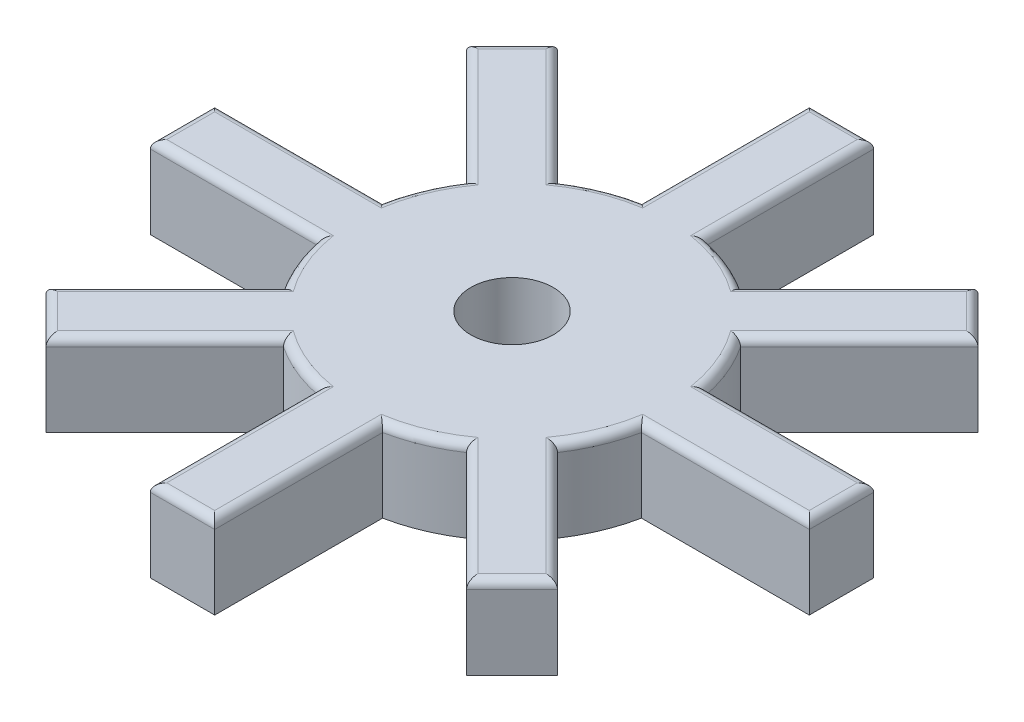
SolidWorks part; units mm, degrees
ref_plane "前视基准面" through (0, 0, 0) normal (0, 0, 1) x (1, 0, 0)
ref_plane "上视基准面" through (0, 0, 0) normal (0, 1, 0) x (1, 0, 0)
ref_plane "右视基准面" through (0, 0, 0) normal (1, 0, 0) x (0, 0, -1)
other "Configuration Table"
sketch "草图1" plane through (0, 0, 0) normal (0, 1, 0) x (1, 0, 0)
  line L0 (0, -20.2795) -> (0, 22.972) construction
  line L1 (1.9541, 9.8072) -> (1.9541, 20)
  line L2 (1.9541, 20) -> (-1.9541, 20)
  line L3 (-1.9541, 9.8072) -> (-1.9541, 20)
  line L4 (8.3165, 5.553) -> (15.5239, 12.7604)
  line L5 (15.5239, 12.7604) -> (12.7604, 15.5239)
  line L6 (5.553, 8.3165) -> (12.7604, 15.5239)
  line L7 (9.8072, -1.9541) -> (20, -1.9541)
  line L8 (20, -1.9541) -> (20, 1.9541)
  line L9 (9.8072, 1.9541) -> (20, 1.9541)
  line L10 (5.553, -8.3165) -> (12.7604, -15.5239)
  line L11 (12.7604, -15.5239) -> (15.5239, -12.7604)
  line L12 (8.3165, -5.553) -> (15.5239, -12.7604)
  line L13 (-1.9541, -9.8072) -> (-1.9541, -20)
  line L14 (-1.9541, -20) -> (1.9541, -20)
  line L15 (1.9541, -9.8072) -> (1.9541, -20)
  line L16 (-8.3165, -5.553) -> (-15.5239, -12.7604)
  line L17 (-15.5239, -12.7604) -> (-12.7604, -15.5239)
  line L18 (-5.553, -8.3165) -> (-12.7604, -15.5239)
  line L19 (-9.8072, 1.9541) -> (-20, 1.9541)
  line L20 (-20, 1.9541) -> (-20, -1.9541)
  line L21 (-9.8072, -1.9541) -> (-20, -1.9541)
  line L22 (-5.553, 8.3165) -> (-12.7604, 15.5239)
  line L23 (-12.7604, 15.5239) -> (-15.5239, 12.7604)
  line L24 (-8.3165, 5.553) -> (-15.5239, 12.7604)
  circle A1 centre (0, 0) radius 10
  circle A2 centre (0, 0) radius 2.5
  point P8 (0, 20)
  point P41 (0, 0)
  dimension "D1" = 8
  dimension "D2" = 40
  dimension "D3" = 20
  dimension "D4" = 5
extrude "凸台-拉伸1" add sketch "草图1" along normal blind 5 contours A1 L22 L23 L24 | A1 L19 L20 L21 | A1 L16 L17 L18 | A1 L0 A2 | L0 A1 A2 | L0 A1 L1 L2 | A1 L0 L2 L3 | A1 L4 L5 L6 | A1 L7 L8 L9 | A1 L10 L11 L12 | L14 L0 A1 L13 | L0 L14 L15 A1
fillet "圆角1" radius 0.5 32 edges at (-14.9036, 5, -1.9541) (3.8268, 5, -9.2388) (9.1567, 5, -11.9202) (14.1421, 5, -14.1421) (11.9202, 5, -9.1567) (9.2388, 5, -3.8268) (14.9036, 5, -1.9541) (20, 5, 0) (14.9036, 5, 1.9541) (9.2388, 5, 3.8268) (11.9202, 5, 9.1567) (14.1421, 5, 14.1421) (9.1567, 5, 11.9202) (3.8268, 5, 9.2388) (1.9541, 5, 14.9036) (0, 5, 20) (-1.9541, 5, 14.9036) (-3.8268, 5, 9.2388) (-9.1567, 5, 11.9202) (-14.1421, 5, 14.1421) (-11.9202, 5, 9.1567) (-9.2388, 5, 3.8268) (-14.9036, 5, 1.9541) (-20, 5, 0) (-9.2388, 5, -3.8268) (-11.9202, 5, -9.1567) (-14.1421, 5, -14.1421) (-9.1567, 5, -11.9202) (-3.8268, 5, -9.2388) (-1.9541, 5, -14.9036) (0, 5, -20) (1.9541, 5, -14.9036)
